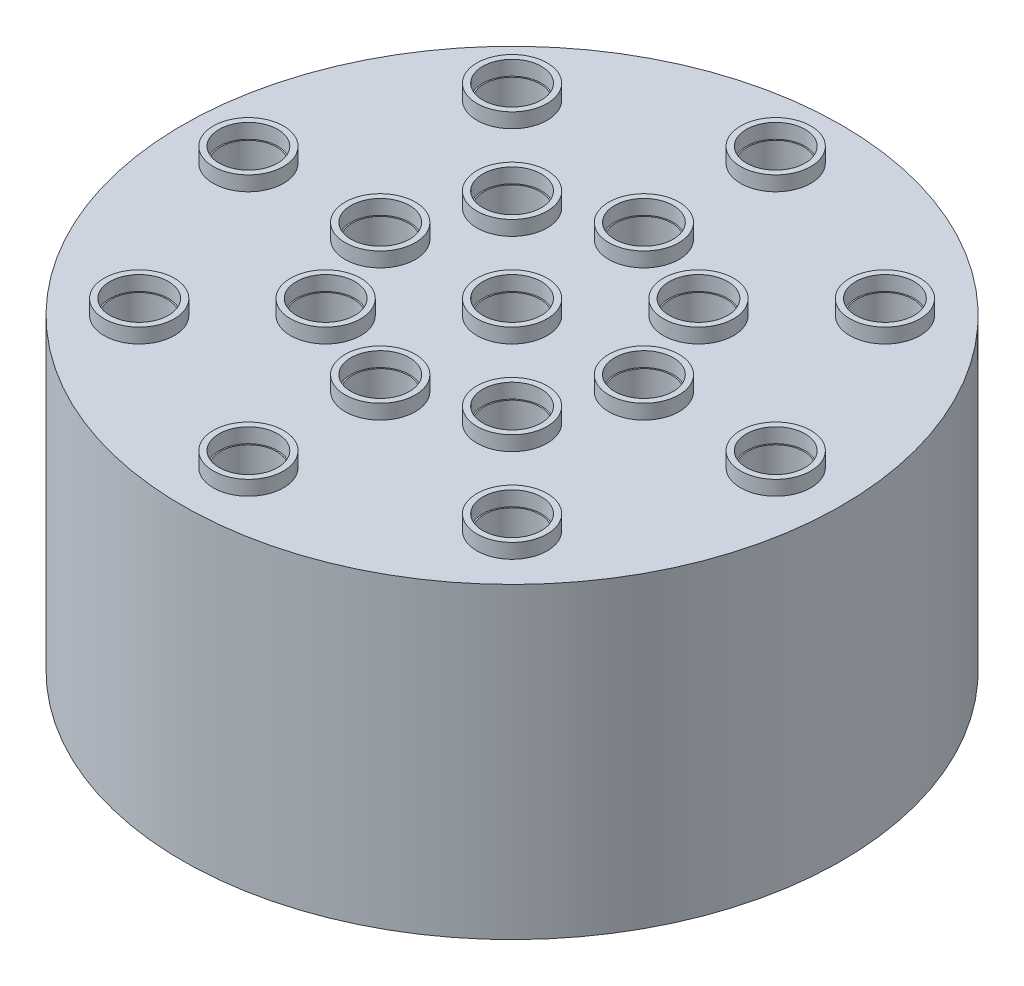
SolidWorks part; units mm, degrees
ref_plane "Front Plane" through (0, 0, 0) normal (0, 0, 1) x (1, 0, 0)
ref_plane "Top Plane" through (0, 0, 0) normal (0, 1, 0) x (1, 0, 0)
ref_plane "Right Plane" through (0, 0, 0) normal (1, 0, 0) x (0, 0, -1)
sketch "Sketch2" plane through (0, 0, 0) normal (0, 1, 0) x (1, 0, 0)
  circle A0 centre (0, 0) radius 45
  dimension "D1" = 90
extrude "Boss-Extrude1" add sketch "Sketch2" along normal blind 42 contours A0
sketch "Sketch6" plane through (0, 42, 0) normal (0, 1, 0) x (1, 0, 0)
  circle A0 centre (0, 0) radius 3.825
  dimension "D1" = 7.65
extrude "Cut-Extrude1" cut sketch "Sketch6" against normal blind 16 contours A0
hole_wizard "CSK for M5 Countersunk Flat Head Screw1" positions "Sketch7" profile "Sketch9" countersink size "M5" standard "ISO"
sketch "Sketch7" plane through (0, 26, 0) normal (0, 1, 0) x (1, 0, 0)
  point P0 (0, 0)
sketch "Sketch9" plane through (0, 26, 0) normal (1, 0, 0) x (0, 0, 1)
  line L0 (0, 0) -> (0, 15.2923)
  line L1 (0, 15.2923) -> (2.65, 13.7)
  line L2 (2.65, 13.7) -> (2.65, 2.55)
  line L3 (2.65, 2.55) -> (5.2, 0)
  line L5 (5.2, 0) -> (0, 0)
  line L6 (-2.65, 2.55) -> (-5.2, 0) construction
  line L10 (0, 15.2923) -> (-2.65, 13.7) construction
  line L11 (0, -6.35) -> (0, 107.95) construction
  dimension "Hole Dia." = 5.3
  dimension "Hole Depth" = 13.7
  dimension "Near C'Sink Dia." = 10.4
  dimension "Near C'Sink Angle" = 90
  dimension "Drill Angle" = 118
sketch "Sketch10" plane through (0, 42, 0) normal (0, 1, 0) x (1, 0, 0)
  circle A0 centre (0, 0) radius 4.7964
extrude "Boss-Extrude2" add sketch "Sketch10" along normal blind 2
sketch "Sketch11" plane through (0, 44, 0) normal (0, 1, 0) x (1, 0, 0)
  circle A0 centre (0, 0) radius 4
extrude "Cut-Extrude2" cut sketch "Sketch11" against normal blind 2
pattern_linear "LPattern1" count 3 spacing 18 along (1, 0, 0) count 3 spacing 18 along (-1, 0, 0) of "Cut-Extrude1", "CSK for M5 Countersunk Flat Head Screw1", "Boss-Extrude2", "Cut-Extrude2"
sketch "Sketch13" plane through (0, 42, 0) normal (0, 1, 0) x (1, 0, 0)
  line L0 (0, 0) -> (0, 45) construction
  line L1 (0, 45) -> (0, -45) construction
  line L2 (0, -45) -> (0, 0) construction
  line L3 (0, 0) -> (45, 0) construction
  line L4 (45, 0) -> (-45, 0) construction
  circle A0 centre (0, 0) radius 45 construction
ref_plane "Plane1" through (0, 0, -45) normal (0, 0, -1) x (-1, 0, 0)
pattern_linear "LPattern2" count 3 spacing 18 along (0, 0, -1) count 3 spacing 18 along (0, 0, 1) of "Cut-Extrude1", "CSK for M5 Countersunk Flat Head Screw1", "Boss-Extrude2", "Cut-Extrude2"
sketch "Sketch14" plane through (0, 42, 0) normal (0, 1, 0) x (1, 0, 0)
  line L0 (0, 0) -> (45, 0) construction
  line L1 (0, 0) -> (-31.8198, 31.8198) construction
  line L2 (-31.8198, 31.8198) -> (31.8198, -31.8198) construction
  line L3 (0, 0) -> (0, 45) construction
  line L4 (0, 0) -> (31.8198, 31.8198) construction
  line L5 (31.8198, 31.8198) -> (-31.8198, -31.8198) construction
  circle A0 centre (0.7584, 0) radius 36.008
  circle A1 centre (0, 0) radius 18
  circle A2 centre (0, 0) radius 45 construction
  dimension "D1" = 45
  dimension "D2" = 45
pattern_linear "LPattern3" count 3 spacing 18 along (-0.7071, 0, 0.7071) count 3 spacing 18 along (0.7071, 0, -0.7071) of "Cut-Extrude1", "CSK for M5 Countersunk Flat Head Screw1", "Boss-Extrude2", "Cut-Extrude2"
pattern_linear "LPattern4" count 3 spacing 18 along (0.7071, 0, 0.7071) count 3 spacing 18 along (-0.7071, 0, -0.7071) of "Cut-Extrude1", "CSK for M5 Countersunk Flat Head Screw1", "Boss-Extrude2", "Cut-Extrude2"
